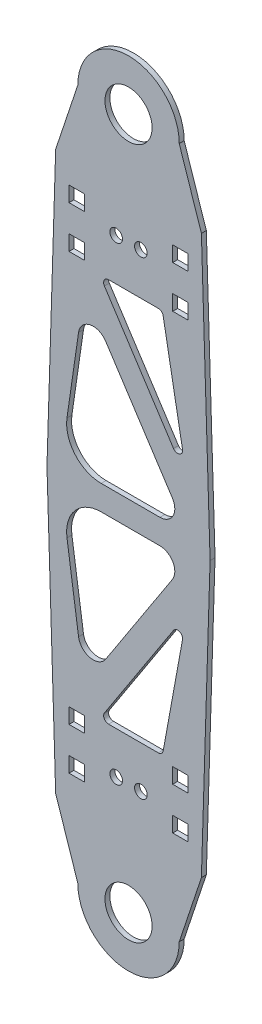
SolidWorks part; units mm, degrees
ref_plane "前视基准面" through (0, 0, 0) normal (0, 0, 1) x (1, 0, 0)
ref_plane "上视基准面" through (0, 0, 0) normal (0, 1, 0) x (1, 0, 0)
ref_plane "右视基准面" through (0, 0, 0) normal (1, 0, 0) x (0, 0, -1)
sketch "草图1" plane through (0, 0, 0) normal (0, 0, 1) x (1, 0, 0)
  line L0 (-30.283, 70.0117) -> (35.7802, 70.0117) construction
  line L1 (-4.7912, 161.5117) -> (-20.2115, 161.5117) construction
  line L18 (-21.3514, 156.0617) -> (-15.1514, 156.0617)
  line L20 (-21.3514, 173.1617) -> (-15.1514, 173.1617)
  line L22 (-21.3514, 173.1617) -> (-21.3514, 166.9617)
  line L23 (-21.3514, 166.9617) -> (-15.1514, 166.9617)
  line L41 (-35.3015, 230.0117) -> (40.7985, 230.0117) construction
  line L42 (-15.1514, 173.1617) -> (-15.1514, 166.9617)
  line L47 (20.6486, 152.9617) -> (35.7802, 70.0117) construction
  line L48 (35.7802, 70.0117) -> (-18.2514, 152.9617) construction
  line L49 (-18.2514, 152.9617) -> (20.6486, 152.9617) construction
  line L50 (26.3995, 93.574) -> (-9.0273, 147.9617)
  line L51 (-9.0273, 147.9617) -> (16.4782, 147.9617)
  line L52 (16.4782, 147.9617) -> (26.3995, 93.574)
  line L53 (-21.3514, 173.1617) -> (-15.1514, 166.9617) construction
  line L54 (-18.2514, 152.9617) -> (-30.283, 70.0117) construction
  line L55 (-15.206, 139.1254) -> (-24.5055, 75.0117)
  line L56 (26.5562, 75.0117) -> (-24.5055, 75.0117)
  line L57 (26.5562, 75.0117) -> (-15.206, 139.1254)
  line L58 (35.7802, 70.0117) -> (-30.283, 70.0117) construction
  line L59 (-21.3514, 166.9617) -> (-15.1514, 173.1617) construction
  line L60 (-21.3514, 149.8617) -> (-21.3514, 156.0617)
  line L61 (-21.3514, 149.8617) -> (-15.1514, 149.8617)
  line L62 (-15.1514, 149.8617) -> (-15.1514, 156.0617)
  line L63 (-17.7794, 210.0117) -> (-26.7611, 183.0084)
  line L64 (-26.7611, 183.0084) -> (-30.283, 70.0117)
  line L65 (2.7486, 210.0117) -> (2.7486, -69.9883) construction
  line L66 (32.2583, 183.0084) -> (35.7802, 70.0117)
  line L67 (23.2767, 210.0117) -> (32.2583, 183.0084)
  line L68 (26.8486, 149.8617) -> (20.6486, 149.8617)
  line L69 (26.8486, 149.8617) -> (26.8486, 156.0617)
  line L70 (26.8486, 156.0617) -> (20.6486, 156.0617)
  line L71 (20.6486, 149.8617) -> (20.6486, 156.0617)
  line L72 (20.6486, 173.1617) -> (20.6486, 166.9617)
  line L73 (26.8486, 173.1617) -> (20.6486, 173.1617)
  line L74 (26.8486, 173.1617) -> (26.8486, 166.9617)
  line L75 (26.8486, 166.9617) -> (20.6486, 166.9617)
  line L76 (-30.283, 70.0117) -> (35.7802, 70.0117) construction
  line L77 (-21.3514, -26.9383) -> (-15.1514, -33.1383) construction
  line L78 (-18.2514, -12.9383) -> (-30.283, 70.0117) construction
  line L79 (-21.3514, -33.1383) -> (-15.1514, -26.9383) construction
  line L80 (-18.2514, -12.9383) -> (20.6486, -12.9383) construction
  line L81 (35.7802, 70.0117) -> (-18.2514, -12.9383) construction
  line L82 (20.6486, -12.9383) -> (35.7802, 70.0117) construction
  line L83 (-35.3015, -89.9883) -> (40.7985, -89.9883) construction
  line L84 (-4.7912, -21.4883) -> (-20.2115, -21.4883) construction
  line L85 (26.8486, -26.9383) -> (20.6486, -26.9383)
  line L86 (26.8486, -33.1383) -> (26.8486, -26.9383)
  line L87 (26.8486, -33.1383) -> (20.6486, -33.1383)
  line L88 (20.6486, -33.1383) -> (20.6486, -26.9383)
  line L89 (20.6486, -9.8383) -> (20.6486, -16.0383)
  line L90 (26.8486, -16.0383) -> (20.6486, -16.0383)
  line L91 (26.8486, -9.8383) -> (26.8486, -16.0383)
  line L92 (26.8486, -9.8383) -> (20.6486, -9.8383)
  line L93 (23.2767, -69.9883) -> (32.2583, -42.985)
  line L94 (32.2583, -42.985) -> (35.7802, 70.0117)
  line L95 (-26.7611, -42.985) -> (-30.283, 70.0117)
  line L96 (-17.7794, -69.9883) -> (-26.7611, -42.985)
  line L97 (-15.1514, -9.8383) -> (-15.1514, -16.0383)
  line L98 (-21.3514, -9.8383) -> (-15.1514, -9.8383)
  line L99 (-21.3514, -9.8383) -> (-21.3514, -16.0383)
  line L100 (26.5562, 65.0117) -> (-15.206, 0.898)
  line L101 (26.5562, 65.0117) -> (-24.5055, 65.0117)
  line L102 (-15.206, 0.898) -> (-24.5055, 65.0117)
  line L103 (16.4782, -7.9383) -> (26.3995, 46.4494)
  line L104 (-9.0273, -7.9383) -> (16.4782, -7.9383)
  line L105 (26.3995, 46.4494) -> (-9.0273, -7.9383)
  line L106 (-15.1514, -33.1383) -> (-15.1514, -26.9383)
  line L107 (-21.3514, -26.9383) -> (-15.1514, -26.9383)
  line L108 (-21.3514, -33.1383) -> (-21.3514, -26.9383)
  line L109 (-21.3514, -33.1383) -> (-15.1514, -33.1383)
  line L110 (-21.3514, -16.0383) -> (-15.1514, -16.0383)
  circle A0 centre (2.7486, 210.0117) radius 9.55
  circle A1 centre (2.7486, 210.0117) radius 40 construction
  circle A2 centre (-2.2514, 165.0117) radius 2.55
  circle A3 centre (7.7486, 165.0117) radius 2.55
  circle A6 centre (2.7486, 210.0117) radius 20.528 construction
  circle A8 centre (2.7486, -69.9883) radius 20.528 construction
  circle A9 centre (2.7486, -69.9883) radius 40 construction
  arc A10 (-17.7794, -69.9883) -> (23.2767, -69.9883) centre (2.7486, -69.9883) ccw
  arc A14 (-17.7794, 210.0117) -> (23.2767, 210.0117) centre (2.7486, 210.0117) cw
  circle A15 centre (7.7486, -24.9883) radius 2.55
  circle A16 centre (-2.2514, -24.9883) radius 2.55
  circle A17 centre (2.7486, -69.9883) radius 9.55
  point P2 (-18.2514, 152.9617)
  point P4 (-18.2514, 170.0617)
  point P13 (0, 0)
  point P16 (0, 0)
  point P28 (-18.2514, 154.5527)
  point P29 (20.6412, 152.9539)
  point P30 (0, 0)
  point P31 (0, 0)
  point P32 (0, 0)
  point P38 (2.7486, 70.0117)
  point P90 (-18.2514, -30.0383)
  point P92 (-18.2514, -12.9383)
  dimension "D10" = 19.1
  dimension "D13" = 80
  dimension "D14" = 5.1
  dimension "D19" = 5
  dimension "D3" = 10
  dimension "D4" = 3.5
  dimension "D5" = 140
  dimension "D7" = 6.2
  dimension "D8" = 6.2
  dimension "D9" = 17.1
  dimension "D11" = 21
  dimension "D12" = 20
  dimension "D15" = 45
  dimension "D16" = 5
  dimension "D20" = 5
extrude "凸台-拉伸2" add sketch "草图1" along normal blind 2 contours A14 L63 L64 L76 L66 L67 L74 L75 L72 L73 L68 L71 L70 L69 L51 L52 L50 L20 L42 L23 L22 L57 L56 L55 L62 L61 L60 L18 A0 A2 A3
fillet "圆角1" radius 6 4 edges at (-15.206, 0.898, 1) (26.5562, 65.0117, 1) (26.5562, 75.0117, 1) (-15.206, 139.1254, 1)
fillet "圆角2" radius 14 2 edges at (-24.5055, 65.0117, 1) (-24.5055, 75.0117, 1)
fillet "圆角3" radius 2 6 edges at (16.4782, -7.9383, 1) (-9.0273, -7.9383, 1) (26.3995, 46.4494, 1) (26.3995, 93.574, 1) (16.4782, 147.9617, 1) (-9.0273, 147.9617, 1)
